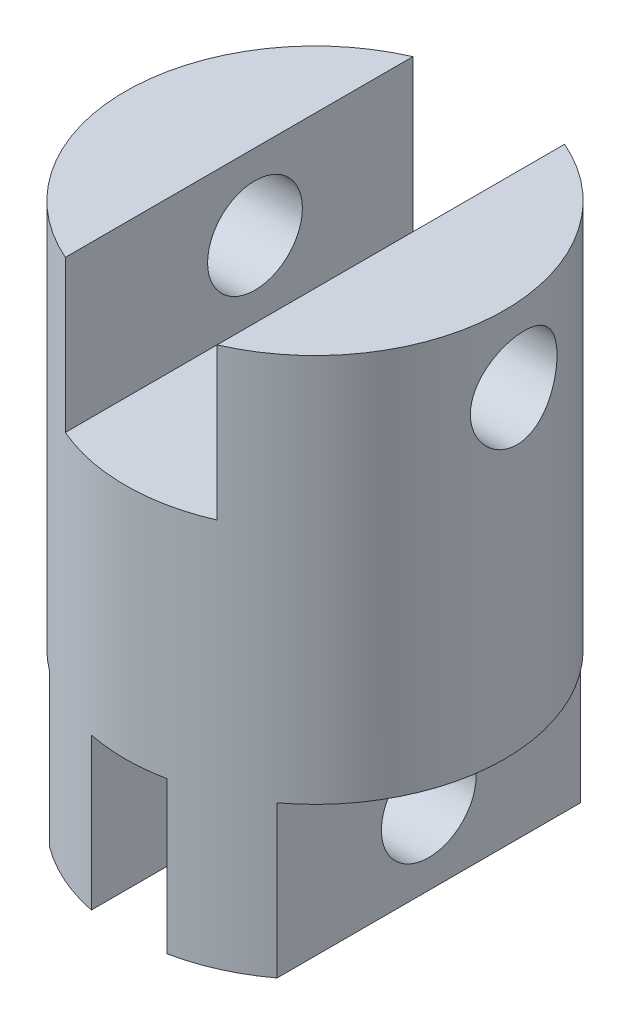
SolidWorks part; units mm, degrees
ref_plane "Front Plane" through (0, 0, 0) normal (0, 0, 1) x (1, 0, 0)
ref_plane "Top Plane" through (0, 0, 0) normal (0, 1, 0) x (1, 0, 0)
ref_plane "Right Plane" through (0, 0, 0) normal (1, 0, 0) x (0, 0, -1)
sketch "Sketch1" plane through (0, 0, 0) normal (0, 1, 0) x (1, 0, 0)
  circle A0 centre (0, 0) radius 12.7
  dimension "D1" = 25.4
extrude "Boss-Extrude1" add sketch "Sketch1" along normal blind 36.195
sketch "Sketch2" plane through (0, 36.195, 0) normal (0, 1, 0) x (1, 0, 0)
  line L0 (5.08, 11.6397) -> (5.08, -11.6397)
  line L1 (-5.08, 11.6397) -> (-5.08, -11.6397)
  arc A0 (-5.08, -11.6397) -> (5.08, -11.6397) centre (0, 0) ccw
  arc A1 (5.08, 11.6397) -> (-5.08, 11.6397) centre (0, 0) ccw
  dimension "D2" = 25.4
  dimension "D1" = 5.08
  dimension "D3" = 5.08
extrude "Cut-Extrude1" cut sketch "Sketch2" against normal blind 10.16
sketch "Sketch3" plane through (0, 0, 0) normal (0, -1, 0) x (1, 0, 0)
  line L0 (-2.54, 12.4434) -> (-2.54, -12.4434)
  line L1 (-7.62, 10.16) -> (-7.62, -10.16)
  line L2 (2.54, 12.4434) -> (2.54, -12.4434)
  line L3 (7.62, 10.16) -> (7.62, -10.16)
  arc A0 (-7.62, 10.16) -> (-7.62, -10.16) centre (0, 0) ccw
  arc A1 (-2.54, -12.4434) -> (2.54, -12.4434) centre (0, 0) ccw
  arc A2 (7.62, -10.16) -> (7.62, 10.16) centre (0, 0) ccw
  arc A3 (2.54, 12.4434) -> (-2.54, 12.4434) centre (0, 0) ccw
  dimension "D1" = 25.4
  dimension "D2" = 2.54
  dimension "D3" = 5.08
  dimension "D4" = 2.54
  dimension "D5" = 5.08
extrude "Cut-Extrude2" cut sketch "Sketch3" against normal blind 10.16
sketch "Sketch4" plane through (-5.08, 0, 0) normal (1, 0, 0) x (0, 0, -1)
  line L0 (11.6397, 36.195) -> (-11.6397, 36.195) construction
  line L5 (10.16, 0) -> (-10.16, 0) construction
  circle A0 centre (1.0603, 31.115) radius 3.175
  circle A2 centre (0, 5.08) radius 3.175
  point P7 (-7.1225, 36.195)
  dimension "D1" = 6.35
  dimension "D3" = 6.35
  dimension "D2" = 5.08
  dimension "D4" = 5.08
extrude "Cut-Extrude3" cut sketch "Sketch4" against normal through all both and the other way through all
sketch "Sketch5" plane through (0, 26.035, 0) normal (0, 1, 0) x (1, 0, 0)
  circle A0 centre (0, 0) radius 2.54
  dimension "D1" = 5.08
extrude "Cut-Extrude4" cut sketch "Sketch5" against normal through all
